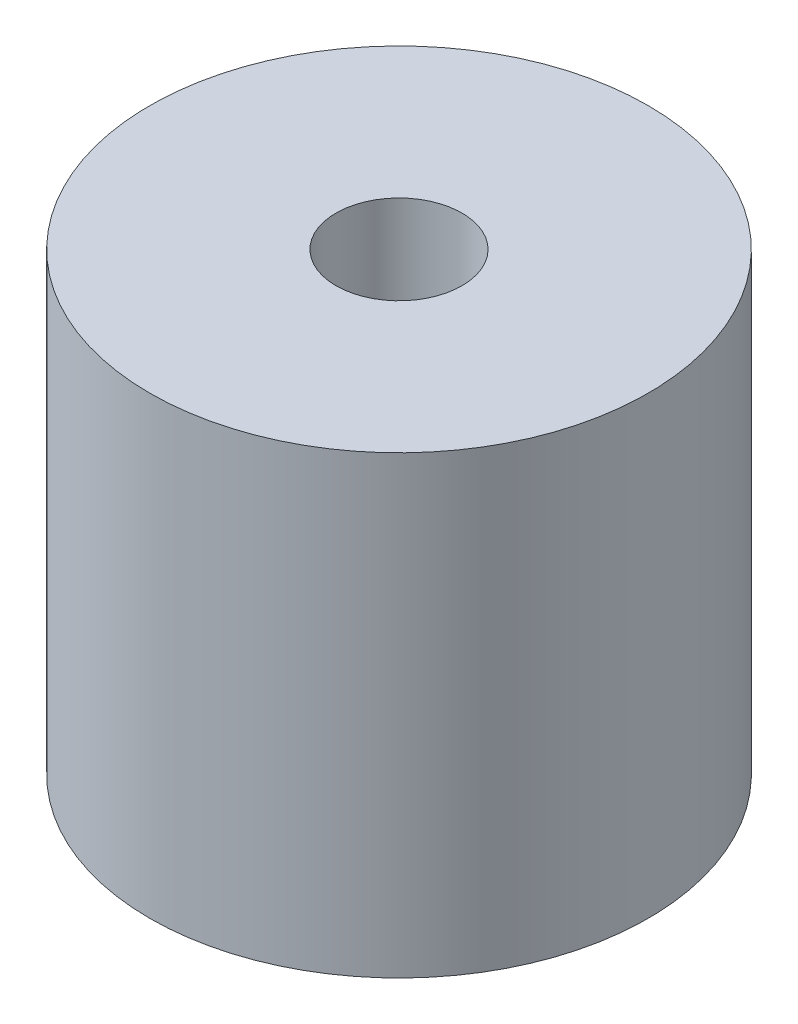
SolidWorks part; units mm, degrees
ref_plane "Front" through (0, 0, 0) normal (0, 0, 1) x (1, 0, 0)
ref_plane "Top" through (0, 0, 0) normal (0, 1, 0) x (1, 0, 0)
ref_plane "Right" through (0, 0, 0) normal (1, 0, 0) x (0, 0, -1)
sketch "Sketch1" plane through (0, 0, 0) normal (0, 1, 0) x (1, 0, 0)
  circle A0 centre (0, 0) radius 8.89
  dimension "D1" = 17.78
extrude "Boss-Extrude1" add sketch "Sketch1" along normal mid plane 16.2306
sketch "Sketch2" plane through (0, 8.1153, 0) normal (0, 1, 0) x (1, 0, 0)
  circle A0 centre (0, 0) radius 2.2479
  dimension "D1" = 4.4958
extrude "Cut-Extrude1" cut sketch "Sketch2" against normal through all both and the other way through all
